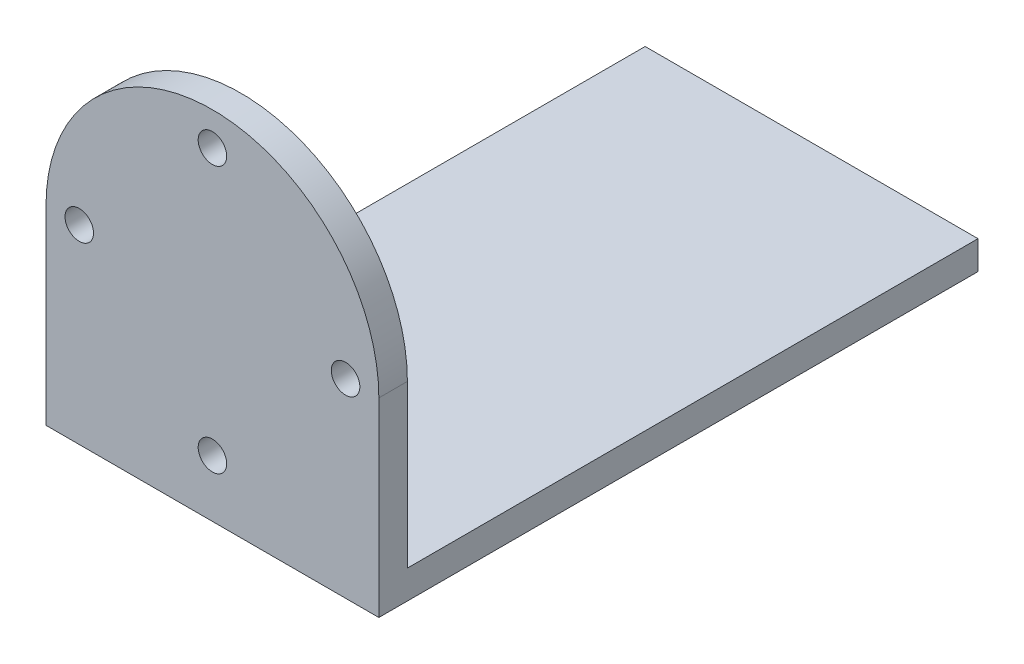
SolidWorks part; units mm, degrees
ref_plane "Front Plane" through (0, 0, 0) normal (0, 0, 1) x (1, 0, 0)
ref_plane "Top Plane" through (0, 0, 0) normal (0, 1, 0) x (1, 0, 0)
ref_plane "Right Plane" through (0, 0, 0) normal (1, 0, 0) x (0, 0, -1)
sketch "Sketch1" plane through (0, 0, 0) normal (0, 0, 1) x (1, 0, 0)
  line L0 (-17.5, 0) -> (-17.5, -20)
  line L1 (-17.5, -20) -> (17.5, -20)
  line L2 (17.5, -20) -> (17.5, 0)
  arc A0 (17.5, 0) -> (-17.5, 0) centre (0, 0) ccw
  circle A1 centre (0, 0) radius 14 construction
  circle A2 centre (0, 14) radius 1.5
  circle A3 centre (0, 14) radius 1.5 construction
  circle A4 centre (14, 0) radius 1.5
  circle A5 centre (0, -14) radius 1.5
  circle A6 centre (-14, 0) radius 1.5
  point P18 (0, 0)
  dimension "D1" = 35
  dimension "D3" = 20
  dimension "D2" = 4
extrude "Boss-Extrude1" add sketch "Sketch1" along normal blind 3
sketch "Sketch2" plane through (0, 0, 0) normal (0, 0, -1) x (-1, 0, 0)
  line L0 (17.5, -20) -> (-17.5, -20)
  line L1 (-17.5, -20) -> (-17.5, -17)
  line L2 (-17.5, -20) -> (-17.5, 0) construction
  line L3 (-17.5, -17) -> (17.5, -17)
  line L4 (17.5, 0) -> (17.5, -20) construction
  line L5 (17.5, -17) -> (17.5, -20)
  dimension "D1" = 3
extrude "Boss-Extrude2" add sketch "Sketch2" along normal blind 60
